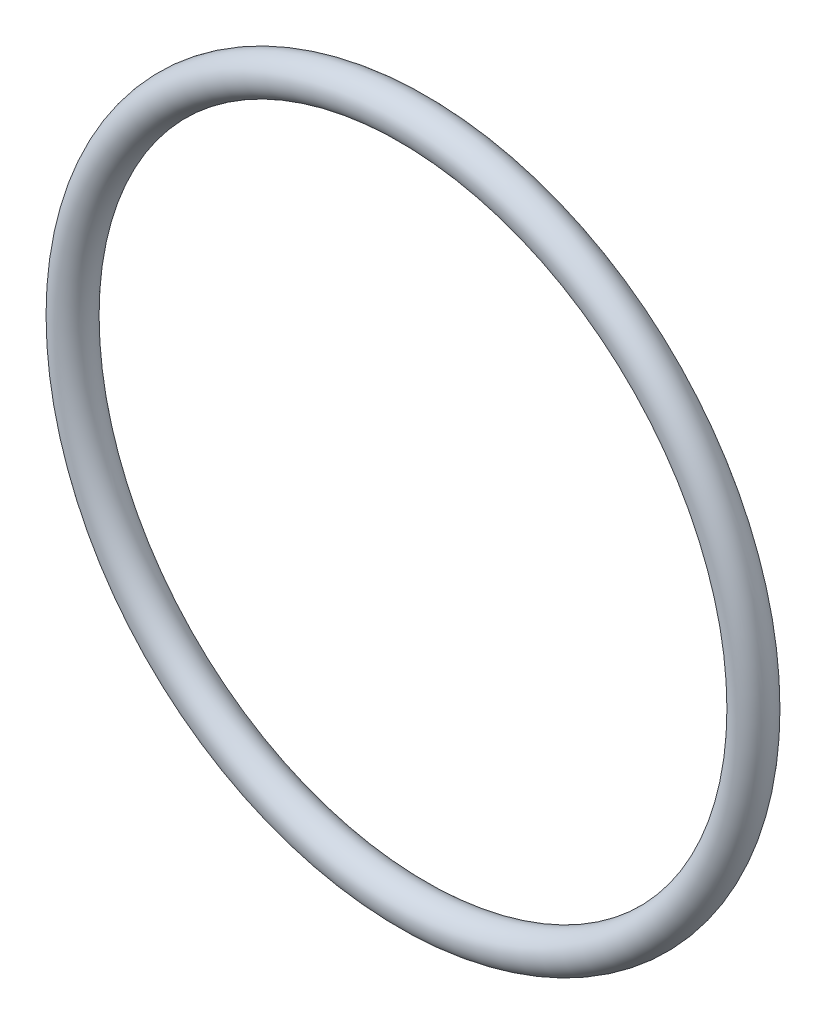
SolidWorks part; units mm, degrees
ref_plane "Front" through (0, 0, 0) normal (0, 0, 1) x (1, 0, 0)
ref_plane "Top" through (0, 0, 0) normal (0, 1, 0) x (1, 0, 0)
ref_plane "Right" through (0, 0, 0) normal (1, 0, 0) x (0, 0, -1)
sketch "Sketch1" plane through (0, 0, 0) normal (1, 0, 0) x (0, -1, 0)
  line L0 (0, -2.667) -> (0, 2.667) construction
  line L2 (-56.1594, 0) -> (56.1594, 0) construction
  line L3 (-45.72, 0) -> (45.72, 0) construction
  circle A0 centre (48.387, 0) radius 2.667
  point P9 (45.72, 0)
  point P10 (51.054, 0)
  point P13 (48.387, 2.667)
  point P14 (48.387, -2.667)
  dimension "Width" = 5.334
  dimension "ID" = 91.44
revolve "Revolve1" add sketch "Sketch1" angle 360 about L0
sketch "Sketch3" plane through (0, 0, 0) normal (0, 0, 1) x (1, 0, 0)
  circle A0 centre (0, 0) radius 18.5615
